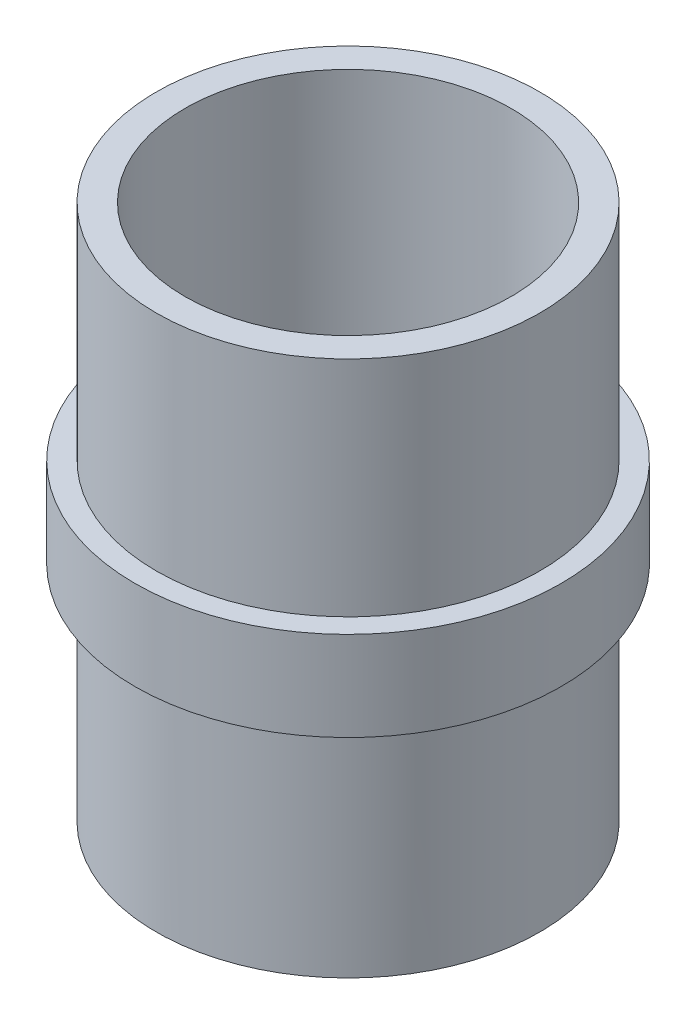
SolidWorks part; units mm, degrees
ref_plane "Front Plane" through (0, 0, 0) normal (0, 0, 1) x (1, 0, 0)
ref_plane "Top Plane" through (0, 0, 0) normal (0, 1, 0) x (1, 0, 0)
ref_plane "Right Plane" through (0, 0, 0) normal (1, 0, 0) x (0, 0, -1)
sketch "Sketch1" plane through (0, 0, 0) normal (0, 1, 0) x (1, 0, 0)
  circle A0 centre (0, 0) radius 10.725
  dimension "D1" = 21.45
extrude "Boss-Extrude1" add sketch "Sketch1" along normal blind 36
ref_plane "Plane1" through (0, 18, 0) normal (0, 1, 0) x (1, 0, 0)
sketch "Sketch2" plane through (0, 18, 0) normal (0, 1, 0) x (1, 0, 0)
  circle A0 centre (0, 0) radius 11.925
  dimension "D1" = 23.85
extrude "Boss-Extrude2" add sketch "Sketch2" along normal blind 2.5 and the other way blind 2.5
sketch "Sketch3" plane through (0, 36, 0) normal (0, 1, 0) x (1, 0, 0)
  circle A0 centre (0, 0) radius 9.125
  circle A1 centre (0, 0) radius 10.725 construction
  dimension "D1" = 1.6
extrude "Cut-Extrude1" cut sketch "Sketch3" against normal blind 33
sketch "Sketch4" plane through (0, 36, 0) normal (0, 1, 0) x (1, 0, 0)
  circle A0 centre (0, 0) radius 10.725
extrude "Cut-Extrude2" cut sketch "Sketch4" against normal blind 3
sketch "Sketch5" plane through (0, 0, 0) normal (0, -1, 0) x (1, 0, 0)
  circle A0 centre (0, 0) radius 10.725
extrude "Cut-Extrude3" cut sketch "Sketch5" against normal blind 3
